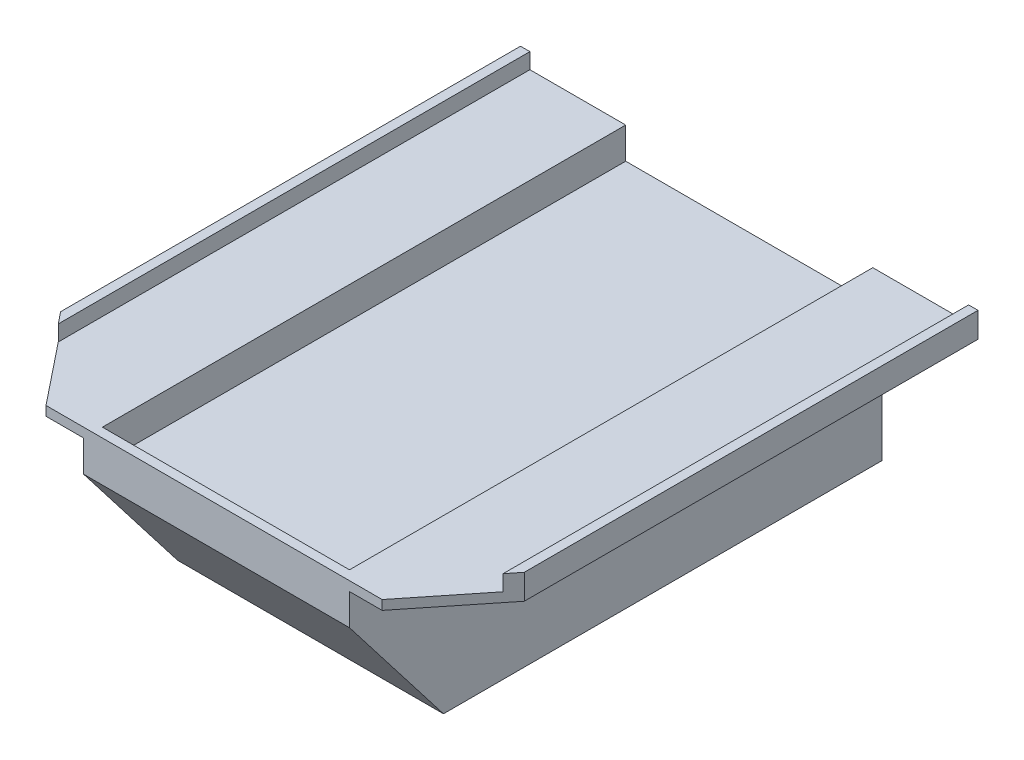
SolidWorks part; units mm, degrees
ref_plane "Ön Düzlem" through (0, 0, 0) normal (0, 0, 1) x (1, 0, 0)
ref_plane "Üst Düzlem" through (0, 0, 0) normal (0, 1, 0) x (1, 0, 0)
ref_plane "Sağ Düzlem" through (0, 0, 0) normal (1, 0, 0) x (0, 0, -1)
sketch "Çizim1" plane through (0, 0, 0) normal (0, 0, 1) x (1, 0, 0)
  line L0 (0, 58.8242) -> (0, -64.0946) construction
  line L1 (-39.425, 0) -> (39.425, 0)
  line L2 (39.425, -38.8) -> (39.425, 0)
  line L3 (-42.425, 10) -> (-73, 10)
  line L4 (-73, 10) -> (-73, 18)
  line L5 (-73, 18) -> (-70, 18)
  line L6 (-70, 18) -> (-70, 13)
  line L7 (-70, 13) -> (-39.425, 13)
  line L8 (42.425, -38.8) -> (39.425, -38.8)
  line L9 (42.425, 10) -> (42.425, -38.8)
  line L10 (39.425, 13) -> (39.425, 3)
  line L11 (-39.425, 13) -> (-39.425, 3)
  line L12 (-39.425, 3) -> (39.425, 3)
  line L13 (-42.425, 10) -> (-42.425, -38.8)
  line L14 (-42.425, -38.8) -> (-39.425, -38.8)
  line L15 (-39.425, -38.8) -> (-39.425, 0)
  line L16 (70, 13) -> (39.425, 13)
  line L17 (70, 18) -> (70, 13)
  line L18 (73, 18) -> (70, 18)
  line L19 (73, 10) -> (73, 18)
  line L20 (42.425, 10) -> (73, 10)
  point P15 (0, 0)
  point P24 (0, 3)
  point P29 (0, 0)
  dimension "D1" = 38.8
  dimension "D2" = 73
  dimension "D3" = 10
  dimension "D4" = 8
  dimension "D5" = 39.425
  dimension "D6" = 3
  dimension "D7" = 3
  dimension "D8" = 3
  dimension "D9" = 3
extrude "Yükseklik-Ekstrüzyon2" add sketch "Çizim1" along normal blind 170
sketch "Çizim2" plane through (0, 0, 0) normal (1, 0, 0) x (0, 0, -1)
  line L0 (-170, -38.8) -> (-170, 0)
  line L1 (-170, 10) -> (-170, -38.8) construction
  line L2 (-170, -38.8) -> (0, -38.8) construction
  line L3 (-140, -38.8) -> (-170, -38.8)
  line L4 (-170, 0) -> (-140, -38.8)
  dimension "D1" = 30
extrude "Kes-Ekstrüzyon1" cut sketch "Çizim2" against normal through all both and the other way through all
sketch "Çizim3" plane through (0, -82.2635, 106.3942) normal (0, -0.6117, 0.7911) x (1, 0, 0)
  line L1 (-39.425, 103.9855) -> (39.425, 103.9855)
  line L2 (-39.425, 103.9855) -> (-39.425, 54.9402)
  line L3 (-39.425, 54.9402) -> (39.425, 54.9402)
  line L4 (39.425, 103.9855) -> (39.425, 54.9402)
extrude "Yükseklik-Ekstrüzyon3" add sketch "Çizim3" against normal blind 3
sketch "Çizim4" plane through (0, 0, 0) normal (0, 1, 0) x (1, 0, 0)
  line L3 (-73, -170) -> (-73, -146.7541)
  line L4 (-54.4218, -170) -> (-73, -170)
  line L5 (0, 0) -> (0, -191.4238) construction
  line L6 (52.86, -170) -> (73, -170)
  line L7 (73, -170) -> (73, -144.8)
  line L8 (73, -144.8) -> (52.86, -170)
  line L9 (-54.4218, -170) -> (-73, -146.7541)
  dimension "D1" = 23.2459
  dimension "D2" = 29.7577
extrude "Kes-Ekstrüzyon3" cut sketch "Çizim4" against normal through all both and the other way through all
sketch "Çizim5" plane through (0, 0, 170) normal (0, 0, 1) x (1, 0, 0)
  line L0 (-42.425, 0) -> (-42.425, 13)
  line L1 (-39.425, 13) -> (-54.4218, 13) construction
  line L2 (-42.425, 0) -> (42.425, 0)
  line L3 (42.425, 0) -> (42.425, 13)
  line L4 (52.86, 13) -> (39.425, 13) construction
  line L5 (42.425, 13) -> (-42.425, 13)
extrude "Yükseklik-Ekstrüzyon4" add sketch "Çizim5" against normal blind 3
